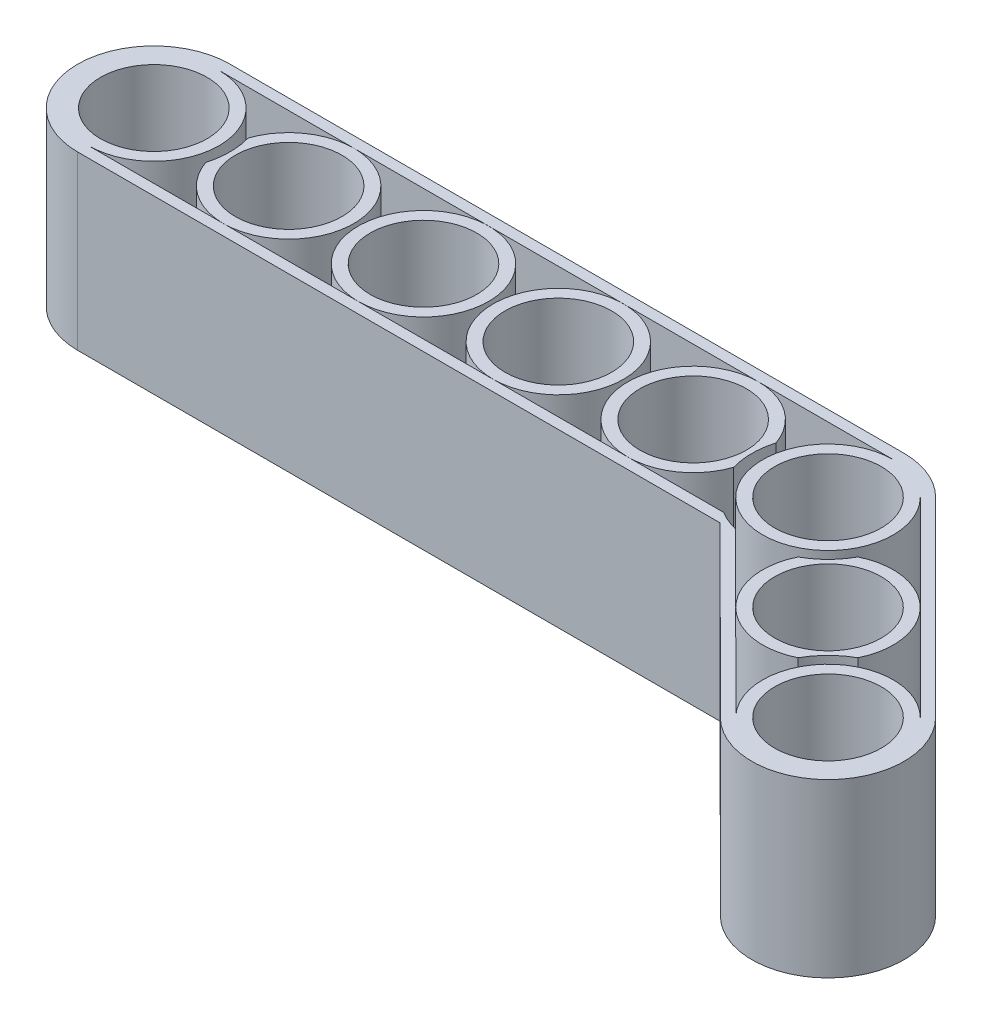
SolidWorks part; units mm, degrees
ref_plane "Front Plane" through (0, 0, 0) normal (0, 0, 1) x (1, 0, 0)
ref_plane "Top Plane" through (0, 0, 0) normal (0, 1, 0) x (1, 0, 0)
ref_plane "Right Plane" through (0, 0, 0) normal (1, 0, 0) x (0, 0, -1)
sketch "Sketch1" plane through (0, 0, 0) normal (0, 1, 0) x (1, 0, 0)
  line L0 (3, 0) -> (34, 0)
  line L1 (0, -3) -> (31, -3)
  line L2 (0, 3) -> (32.2426, 3)
  line L3 (31, 0) -> (40.0169, -9.0169)
  line L4 (39.7681, -8.7681) -> (37.5555, -10.7941) construction
  line L5 (32.2426, 3) -> (42.1221, -6.8794)
  line L6 (35.3841, -4.3841) -> (44.401, -13.401)
  line L7 (39.7681, -8.7681) -> (48.785, -17.785)
  line L8 (37.5555, -10.7941) -> (29.754, -3)
  line L9 (0, -3.5) -> (29.5416, -3.5)
  line L10 (29.5416, -3.5) -> (37.2946, -11.2444)
  line L11 (0, 3.5) -> (31, 3.5)
  line L12 (42.243, -6.2933) -> (33.4749, 2.4749)
  circle A0 centre (0, 0) radius 2.45
  circle A1 centre (0, 0) radius 3
  circle A2 centre (6.2, 0) radius 3
  circle A3 centre (6.2, 0) radius 2.45
  circle A4 centre (12.4, 0) radius 3
  circle A5 centre (12.4, 0) radius 2.45
  circle A6 centre (18.6, 0) radius 3
  circle A7 centre (18.6, 0) radius 2.45
  circle A8 centre (24.8, 0) radius 3
  circle A9 centre (24.8, 0) radius 2.45
  circle A10 centre (31, 0) radius 3
  circle A11 centre (31, 0) radius 2.45
  circle A12 centre (35.3841, -4.3841) radius 3
  circle A13 centre (35.3841, -4.3841) radius 2.45
  circle A14 centre (39.7681, -8.7681) radius 3
  circle A15 centre (39.7681, -8.7681) radius 2.45
  circle A16 centre (0, 0) radius 3.5
  circle A17 centre (39.7681, -8.7681) radius 3.5
  circle A18 centre (31, 0) radius 3.5
  dimension "D1" = 4.9
  dimension "D2" = 6
  dimension "D8" = 7
  dimension "D9" = 7
  dimension "D10" = 7
  dimension "D3" = 31
  dimension "D5" = 135
  dimension "D6" = 31
  dimension "D7" = 3
  dimension "D4" = 6
extrude "Boss-Extrude1" add sketch "Sketch1" along normal blind 7.9
